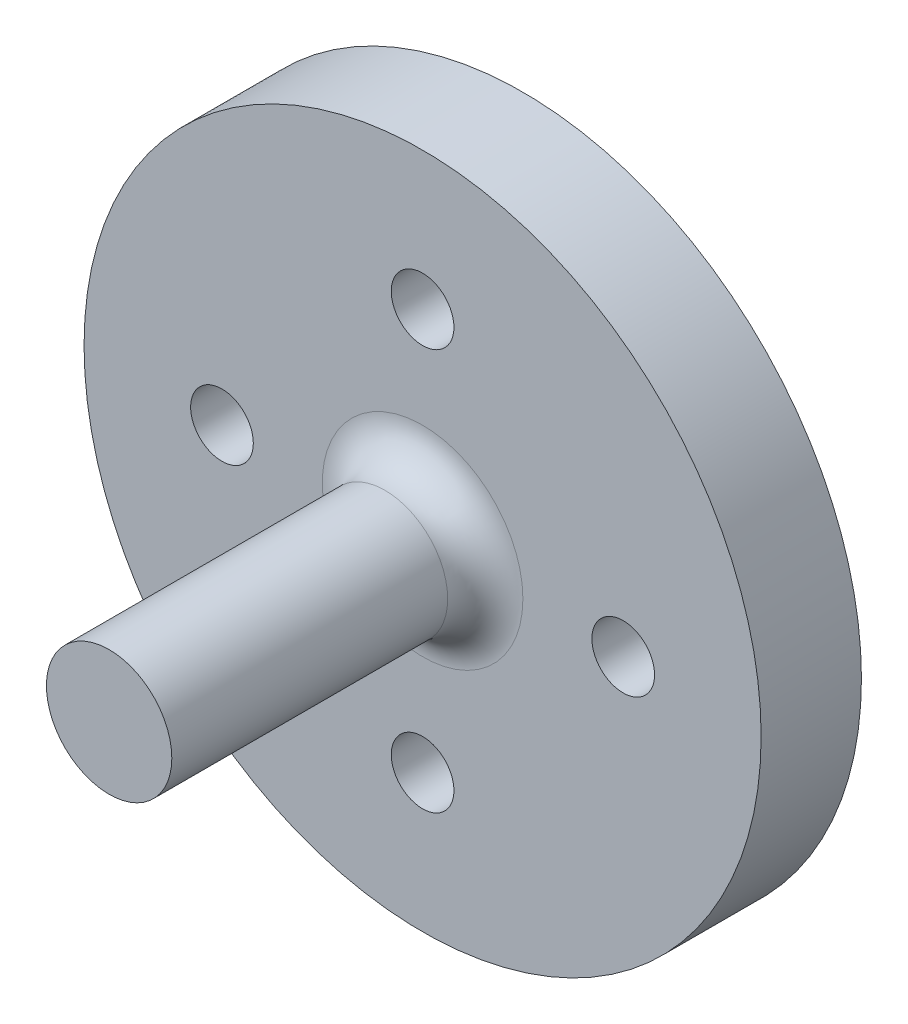
SolidWorks part; units mm, degrees
material "Alumina"
ref_plane "Front Plane" through (0, 0, 0) normal (0, 0, 1) x (1, 0, 0)
ref_plane "Top Plane" through (0, 0, 0) normal (0, 1, 0) x (1, 0, 0)
ref_plane "Right Plane" through (0, 0, 0) normal (1, 0, 0) x (0, 0, -1)
sketch "Sketch1" plane through (0, 0, 0) normal (0, 0, 1) x (1, 0, 0)
  circle A0 centre (0, 0) radius 27
  dimension "D1" = 54
extrude "Boss-Extrude1" add sketch "Sketch1" along normal blind 8 contours A0
sketch "Sketch2" plane through (0, 0, 8) normal (0, 0, 1) x (1, 0, 0)
  circle A0 centre (0, 0) radius 16 construction
  circle A1 centre (-16, 0) radius 2.5
  circle A2 centre (0, 16) radius 2.5
  circle A3 centre (16, 0) radius 2.5
  circle A4 centre (0, -16) radius 2.5
  dimension "D1" = 5
  dimension "D2" = 32
extrude "Cut-Extrude1" cut sketch "Sketch2" against normal blind 8
sketch "Sketch3" plane through (0, 0, 8) normal (0, 0, 1) x (1, 0, 0)
  circle A0 centre (0, 0) radius 5
  dimension "D1" = 10
extrude "Boss-Extrude2" add sketch "Sketch3" along normal blind 25
fillet "Fillet1" radius 3 1 edges at (5, 0, 8)
